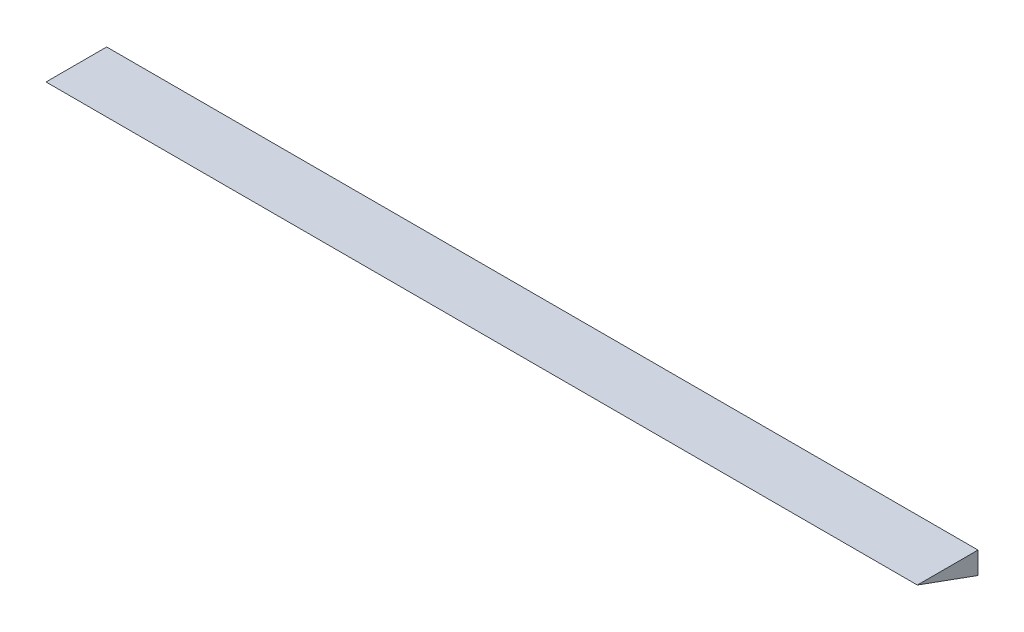
SolidWorks part; units mm, degrees
ref_plane "Front" through (0, 0, 0) normal (0, 0, 1) x (1, 0, 0)
ref_plane "Top" through (0, 0, 0) normal (0, 1, 0) x (1, 0, 0)
ref_plane "Right" through (0, 0, 0) normal (1, 0, 0) x (0, 0, -1)
sketch "草图1" plane through (0, 0, 0) normal (1, 0, 0) x (0, 0, -1)
  line L0 (0, 0) -> (7.5175, -2.7362)
  line L2 (0, 0) -> (7.5175, 0)
  line L3 (7.5175, 0) -> (7.5175, -2.7362)
  dimension "D1" = 8
  dimension "D2" = 20
extrude "凸台-拉伸1" add sketch "草图1" along normal blind 108
